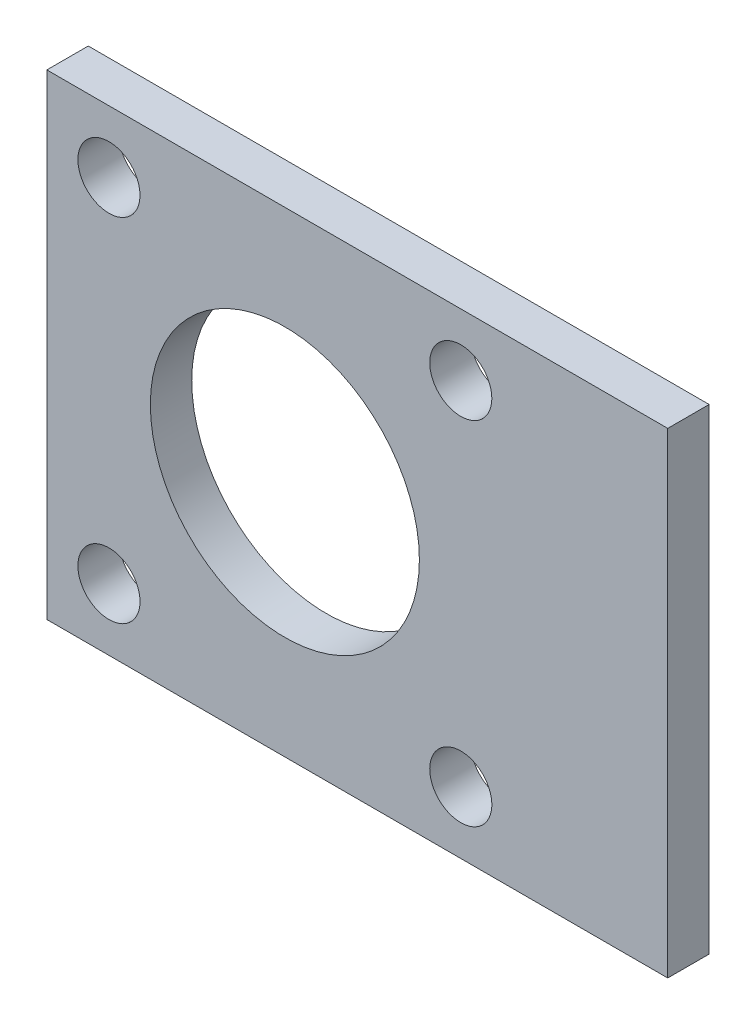
SolidWorks part; units mm, degrees
ref_plane "Plano frontal" through (0, 0, 0) normal (0, 0, 1) x (1, 0, 0)
ref_plane "Plano superior" through (0, 0, 0) normal (0, 1, 0) x (1, 0, 0)
ref_plane "Plano direito" through (0, 0, 0) normal (1, 0, 0) x (0, 0, -1)
sketch "Esboço1" plane through (0, 0, 0) normal (0, 0, 1) x (1, 0, 0)
  line L0 (15, 11.5) -> (-15, -11.5) construction
  line L1 (-15, 11.5) -> (15, 11.5)
  line L2 (-15, 11.5) -> (-15, -11.5)
  line L3 (-15, -11.5) -> (15, -11.5)
  line L4 (15, 11.5) -> (15, -11.5)
  dimension "D1" = 23
  dimension "D2" = 30
extrude "Ressalto-extrusão1" add sketch "Esboço1" along normal blind 2
sketch "Esboço2" plane through (0, 0, 2) normal (0, 0, 1) x (1, 0, 0)
  line L0 (8, 11.5) -> (8, -11.5) construction
  line L1 (15, 11.5) -> (-15, 11.5) construction
  line L2 (-15, -11.5) -> (15, -11.5) construction
  line L3 (-15, 11.5) -> (-15, -11.5) construction
  line L4 (8, 11.5) -> (-15, -11.5) construction
  line L5 (-3.5, 0) -> (-3.5, 11.5) construction
  line L6 (-3.5, 0) -> (8, 0) construction
  line L7 (-3.5, 0) -> (-15, 0) construction
  circle A0 centre (-3.5, 0) radius 6.5
  circle A1 centre (5, 8.5) radius 1.5
  circle A2 centre (5, -8.5) radius 1.5
  circle A3 centre (-3.5, 0) radius 9 construction
  circle A4 centre (-12, -8.5) radius 1.5
  circle A5 centre (-12, 8.5) radius 1.5
  dimension "D2" = 13
  dimension "D3" = 3
  dimension "D5" = 18
  dimension "D1" = 23
  dimension "D4" = 3
extrude "Corte-extrusão1" cut sketch "Esboço2" against normal through all
